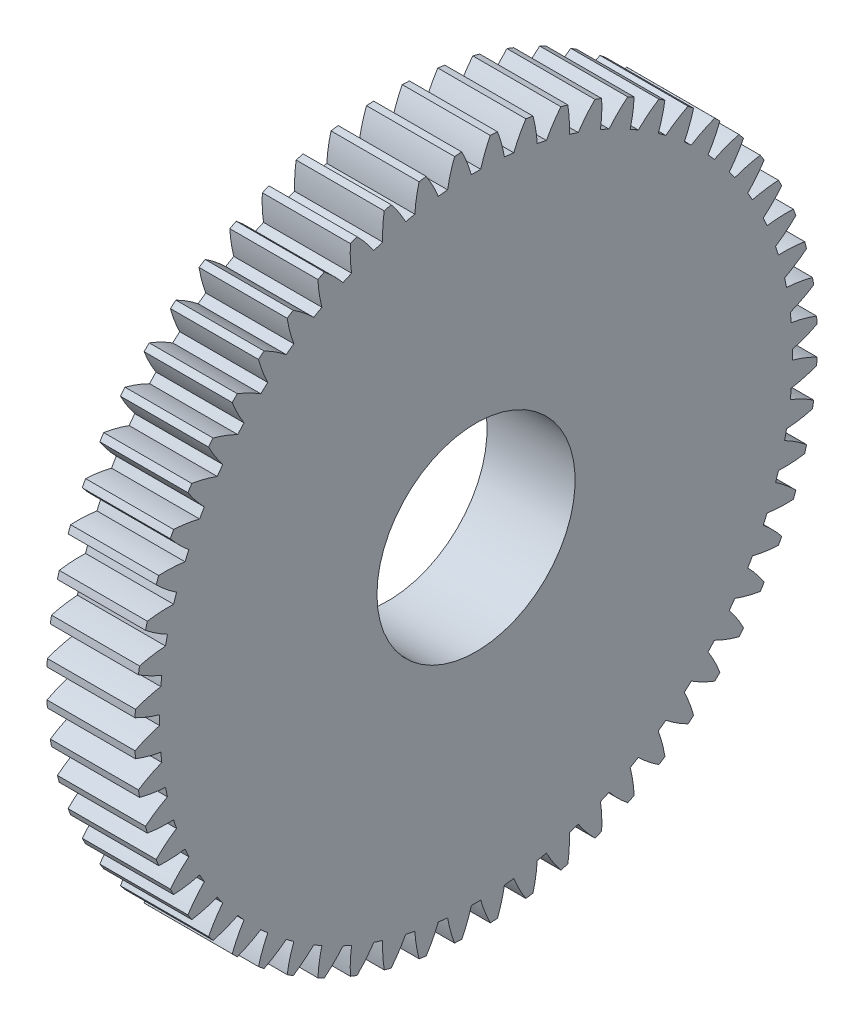
SolidWorks part; units mm, degrees
ref_plane "Plane1" through (0, 0, 0) normal (0, 0, 1) x (1, 0, 0)
ref_plane "Plane2" through (0, 0, 0) normal (0, 1, 0) x (1, 0, 0)
ref_plane "Plane3" through (0, 0, 0) normal (1, 0, 0) x (0, 0, -1)
other "Configuration Table"
sketch "HoldingSke" plane through (0, 0, 0) normal (0, 1, 0) x (1, 0, 0)
  line L0 (0, 0) -> (0.4, -0.6928)
  line L1 (-15, 0) -> (100, 0) construction
  line L2 (0, 0) -> (-2.1039, 2.3779)
  line L3 (0, 0) -> (-11.863, 4.5341)
  line L4 (0, 0) -> (4.318, 7.479)
  line L5 (0, 0) -> (-9.3695, -3.4946)
  line L6 (0, 0) -> (-8.2896, -5.593)
  line L7 (-2.1039, 2.3779) -> (0.0486, 12.1435)
  line L8 (-76.2, 54.61) -> (-73.4, 54.61)
  line L9 (-71.009, 38.7566) -> (-53.1078, 45.2721)
  line L10 (-76.2, 71.12) -> (104.1128, 71.12)
  line L11 (0, 0) -> (-10, 0)
  line L12 (-76.2, 101.6) -> (-76.155, 101.6)
  line L13 (24.9733, 27.94) -> (52.9518, 28.4284)
  line L14 (24.9733, 27.94) -> (24.9743, 27.94)
  line L15 (24.9733, 27.94) -> (100.4006, 29.5858)
  line L16 (-63.627, -1.25) -> (-12.827, -1.25)
  circle A0 centre (0, 0) radius 8.5
  circle A1 centre (0, 0) radius 5
  circle A2 centre (0, 0) radius 5
  circle A3 centre (0, 0) radius 8.5
  dimension "MHD" = 10
  dimension "Hub_dia" = 10
  dimension "Bore" = 17
  dimension "MBD" = 17
  dimension "Num_teeth" = 60
  dimension "Pitch" = 0.8
  dimension "Overall_len" = 10
  dimension "Show_teeth" = 60
  dimension "Thickness" = 10
  dimension "OAL" = 10.0001
  dimension "T_dim" = 2.8
  dimension "Ap" = 20
  dimension "H" = 19.05
  dimension "Pitch_radius" = 180.3128
  dimension "Width" = 10
  dimension "Backlash" = 0.045
  dimension "Addendum_fac" = 1
  dimension "Dedendum_fac" = 1.25
  dimension "Clearance_fac" = 0.25
  dimension "Dedendum_add" = 0.001
  dimension "Module" = 1.25
sketch "BasProSke" plane through (0, 0, 0) normal (0, 1, 0) x (1, 0, 0)
  line L0 (-10, 0) -> (60, 0) construction
  line L1 (0, 0) -> (0, 38.75)
  line L2 (0, 0) -> (10, 0)
  line L3 (10, 0) -> (10, 38.75)
  line L4 (10, 38.75) -> (0, 38.75)
  dimension "Thickness" = 10
  dimension "Diameter" = 77.5
revolve "Base-Revolve" add sketch "BasProSke" angle 360 about L0
sketch "TooCutSke" plane through (0, 0, 0) normal (1, 0, 0) x (0, 0, -1)
  line L1 (0, 0) -> (0, 107) construction
  line L2 (0, 0) -> (-1.0604, 37.485) construction
  line L3 (0, 0) -> (-3.9241, 74.8755) construction
  line L4 (-1.0604, 37.485) -> (-1.962, 37.4378) construction
  arc A0 (0.5336, 35.9325) -> (-0.5336, 35.9325) centre (0, 0) ccw
  arc A1 (1.6331, 38.741) -> (-1.6331, 38.741) centre (0, 0) ccw
  circle A2 centre (0, 0) radius 37.5 construction
  circle A3 centre (0, 0) radius 35.2385 construction
  arc A4 (-0.5336, 35.9325) -> (-1.6331, 38.741) centre (-14.9802, 31.8958) ccw
  arc A5 (1.6331, 38.741) -> (0.5336, 35.9325) centre (14.9802, 31.8958) ccw
  dimension "Root_dia" = 71.873
  dimension "Overcut_dia" = 77.5508
  dimension "Pitch_dia" = 75
  dimension "Base_dia" = 70.4769
  dimension "Flank_rad" = 15
  dimension "Half_ang" = 3
  dimension "Half_CT" = 0.9029
extrude "ToothCut" cut sketch "TooCutSke" along normal through all
fillet "Breaks" [suppressed] radius 0.025
fillet "RootFillets" [suppressed] radius 0.3135
pattern_circular "TeethCuts" count 60 every 6 about axis through (-10, 0, 0) along (1, 0, 0) of "ToothCut", "RootFillets", "Breaks"
sketch "HubNeaOneSke" plane through (0, 0, 0) normal (-1, 0, 0) x (0, 0, 1)
  circle A0 centre (0, 0) radius 5
  dimension "Diameter" = 10
extrude "HubNearOne" add sketch "HubNeaOneSke" along normal blind 5.0001
sketch "HubNeaBotSke" plane through (0, 0, 0) normal (-1, 0, 0) x (0, 0, 1)
  circle A0 centre (0, 0) radius 5
  dimension "Diameter" = 10
extrude "HubNearBoth" [suppressed] add sketch "HubNeaBotSke" along normal blind 2.5
ref_plane "FarPln" through (10, 0, 0) normal (1, 0, 0) x (0, 0, -1)
sketch "HubFarSke" plane through (10, 0, 0) normal (1, 0, 0) x (0, 0, -1)
  circle A0 centre (0, 0) radius 5
  dimension "Diameter" = 10
extrude "HubFar" [suppressed] add sketch "HubFarSke" along normal blind 2.5
sketch "BorSke" plane through (0, 0, 0) normal (1, 0, 0) x (0, 0, -1)
  circle A0 centre (0, 0) radius 8.5
  dimension "Diameter" = 17
extrude "Bore" cut sketch "BorSke" along normal mid plane 20.0001
sketch "KeySke" plane through (0, 0, 0) normal (1, 0, 0) x (0, 0, -1)
  line L0 (-3, 0) -> (-3, 11.3)
  line L1 (-3, 11.3) -> (3, 11.3)
  line L2 (3, 11.3) -> (3, 0)
  line L3 (0, 0) -> (0, 34) construction
  line L4 (-3, 0) -> (3, 0)
  dimension "Offset" = 11.3
  dimension "Width" = 6
extrude "Keyway" [suppressed] cut sketch "KeySke" along normal mid plane 20.0001
pattern_circular "Keyway2" [suppressed] count 2 every 90 about axis through (-10, 0, 0) along (1, 0, 0)
sketch "Sketch1" plane through (0, 0, 0) normal (-1, 0, 0) x (0, 0, 1)
  circle A0 centre (0, 0) radius 11.25
  dimension "D1" = 22.5
extrude "Cut-Extrude1" cut sketch "Sketch1" against normal blind 10
equation "' \"Module@HoldingSke\" = 6.35"
equation "' \"Num_teeth@HoldingSke\" = 12"
equation "' \"Ap@HoldingSke\" =  20"
equation "' \"Ap@HoldingSke\" = 20"
equation "' \"Width@HoldingSke\" = 0.5 * 25.4"
equation "' \"Hub_dia@HoldingSke\"= 1 * 25.4"
equation "' \"Hub_dia@HoldingSke\" = 1 * 25.4"
equation "' \"Overall_len@HoldingSke\" = 1.0 * 25.4"
equation "' \"Bore@HoldingSke\" = 0.75 * 25.4"
equation "' \"T_dim@HoldingSke\" = 0.1 * 25.4"
equation "' \"Width@KeySke\" = 0.25 * 25.4"
equation "' \"Show_teeth@HoldingSke\" = 13"
equation "' \"Backlash@HoldingSke\" = 0.009 * 25.4"
equation "' \"Addendum_fac@HoldingSke\" = 1.0"
equation "' \"Dedendum_fac@HoldingSke\" = 1.25"
equation "' \"Dedendum_add@HoldingSke\" = 0.00005 * 25.4"
equation "' \"Clearance_fac@HoldingSke\" = 0.25"
equation "\"Pitch@HoldingSke\" = 1 / \"Module@HoldingSke\""
equation "\"Overcut_dia@TooCutSke\" = (\"Num_teeth@HoldingSke\" + 2 * \"Addendum_fac@HoldingSke\") / \"Pitch@HoldingSke\" + 0.002 * 25.4"
equation "\"Pitch_dia@TooCutSke\" = \"Num_teeth@HoldingSke\" / \"Pitch@HoldingSke\""
equation "\"Base_dia@TooCutSke\" = \"Num_teeth@HoldingSke\" / \"Pitch@HoldingSke\" * cos((\"Ap@HoldingSke\"  * 3.14159265 / 180))"
equation "\"Root_dia@TooCutSke\" = (\"Num_teeth@HoldingSke\" + 2) / \"Pitch@HoldingSke\" - 2 * (\"Addendum_fac@HoldingSke\" + \"Dedendum_fac@HoldingSke\") / \"Pitch@HoldingSke\" - \"Dedendum_add@HoldingSke\" * 2"
equation "\"Half_ang@TooCutSke\" = 180 / \"Num_teeth@HoldingSke\""
equation "\"Half_CT@TooCutSke\" = \"Num_teeth@HoldingSke\" / \"Pitch@HoldingSke\" * sin((3.14159265 / 2 / \"Num_teeth@HoldingSke\")) / 2 - 7 * \"Backlash@HoldingSke\" / 4"
equation "\"Flank_rad@TooCutSke\" = \"Num_teeth@HoldingSke\" / \"Pitch@HoldingSke\" / 5"
equation "\"Radius@RootFillets\" = \"Clearance_fac@HoldingSke\" / \"Pitch@HoldingSke\" + \"Dedendum_add@HoldingSke\""
equation "\"Break_rad@Breaks\" = 0.02 / \"Pitch@HoldingSke\""
equation "\"Thickness@HoldingSke\" = \"Width@HoldingSke\""
equation "\"OAL@HoldingSke\" = \"Thickness@HoldingSke\""
equation "\"MHD@HoldingSke\" = (\"Num_teeth@HoldingSke\" + 2) / \"Pitch@HoldingSke\" - 2 * (\"Addendum_fac@HoldingSke\" + \"Dedendum_fac@HoldingSke\")  / \"Pitch@HoldingSke\" - \"Dedendum_add@HoldingSke\" * 2"
equation "\"MBD@HoldingSke\" = (\"Num_teeth@HoldingSke\" + 2) / \"Pitch@HoldingSke\" - 2 * (\"Addendum_fac@HoldingSke\" + \"Dedendum_fac@HoldingSke\")  / \"Pitch@HoldingSke\" - \"Dedendum_add@HoldingSke\" * 2 - 0.002 * 25.4"
equation "\"MHD@HoldingSke\" = ((sgn( \"MHD@HoldingSke\" - \"Hub_dia@HoldingSke\" )-1)*( \"MHD@HoldingSke\" - \"Hub_dia@HoldingSke\" ))/-2+ \"Hub_dia@HoldingSke\""
equation "\"MBD@HoldingSke\" = ((sgn( \"MBD@HoldingSke\" - \"Bore@HoldingSke\" )-1)*( \"MBD@HoldingSke\" - \"Bore@HoldingSke\" ))/-2+ \"Bore@HoldingSke\""
equation "\"OAL@HoldingSke\" = ((sgn( \"OAL@HoldingSke\" - \"Overall_len@HoldingSke\" )+1)*( \"OAL@HoldingSke\" - \"Overall_len@HoldingSke\" ))/2 + \"Overall_len@HoldingSke\" + 0.000002 * 25.4"
equation "\"Num_teeth@TeethCuts\" = int( \"Show_teeth@HoldingSke\" ) + 1"
equation "\"Num_teeth@TeethCuts\" = ((sgn( \"Num_teeth@TeethCuts\" - \"Num_teeth@HoldingSke\" )-1)*( \"Num_teeth@TeethCuts\" - \"Num_teeth@HoldingSke\" ))/-2+ \"Num_teeth@HoldingSke\""
equation "\"Num_teeth@TeethCuts\" = ((sgn( \"Num_teeth@TeethCuts\" - 2.0)+1)*( \"Num_teeth@TeethCuts\" - 2.0))/2 +2.0"
equation "\"Angle@TeethCuts\" = 360.0 / \"Num_teeth@HoldingSke\""
equation "\"Diameter@BasProSke\" = (\"Num_teeth@HoldingSke\" + 2 * \"Addendum_fac@HoldingSke\") / \"Pitch@HoldingSke\""
equation "\"Thickness@BasProSke\"  = \"Thickness@HoldingSke\""
equation "' \"Fillet_rad@BasProSke\" =  \"Thickness@HoldingSke\" * 0.05"
equation "' \"Fillet_rad@BasProSke\" = \"Thickness@HoldingSke\" * 0.05"
equation "\"MHD@HoldingSke\" = ((sgn( \"MHD@HoldingSke\" - \"Root_dia@TooCutSke\" )-1)*( \"MHD@HoldingSke\" - \"Root_dia@TooCutSke\" ))/-2+ \"Root_dia@TooCutSke\""
equation "\"Diameter@HubNeaOneSke\" = \"MHD@HoldingSke\""
equation "\"Length@HubNearOne\" = \"OAL@HoldingSke\" - \"Thickness@BasProSke\""
equation "\"Diameter@HubNeaBotSke\" = \"MHD@HoldingSke\""
equation "\"Length@HubNearBoth\" = ( \"OAL@HoldingSke\" - \"Thickness@BasProSke\" ) / 2.0"
equation "\"Thickness@FarPln\" = \"Thickness@BasProSke\""
equation "\"Diameter@HubFarSke\" = \"MHD@HoldingSke\""
equation "\"Length@HubFar\" = ( \"OAL@HoldingSke\" - \"Thickness@BasProSke\" ) / 2.0"
equation "\"Diameter@BorSke\" = \"MBD@HoldingSke\""
equation "\"D1@Bore\" = \"OAL@HoldingSke\" * 2.0"
equation "\"D1@Keyway\" = \"OAL@HoldingSke\" * 2.0"
equation "\"Offset@KeySke\" = \"T_dim@HoldingSke\" + \"MBD@HoldingSke\" / 2.0"
